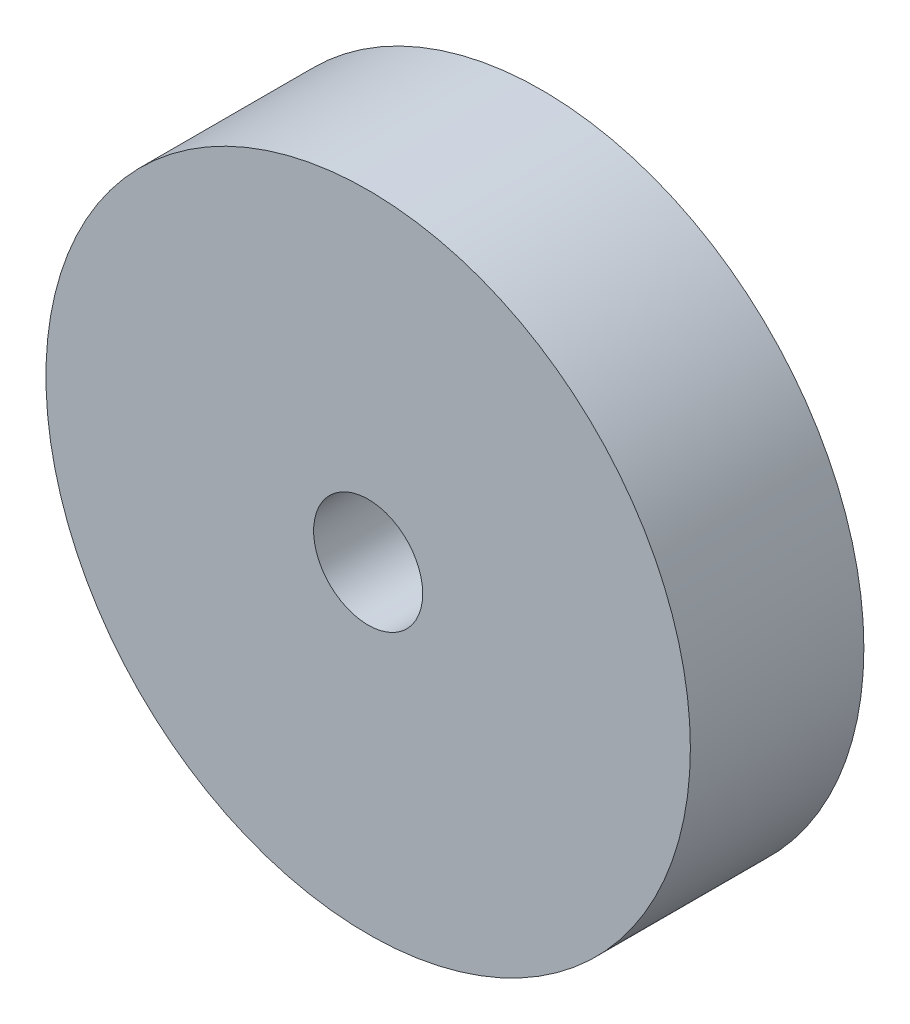
SolidWorks part; units mm, degrees
ref_plane "Front Plane" through (0, 0, 0) normal (0, 0, 1) x (1, 0, 0)
ref_plane "Top Plane" through (0, 0, 0) normal (0, 1, 0) x (1, 0, 0)
ref_plane "Right Plane" through (0, 0, 0) normal (1, 0, 0) x (0, 0, -1)
sketch "Sketch1" plane through (0, 0, 0) normal (0, 0, 1) x (1, 0, 0)
  circle A0 centre (-59.8968, 23.1083) radius 13
  circle A1 centre (-59.8968, 23.1083) radius 1.5
extrude "Boss-Extrude1" add sketch "Sketch1" along normal blind 8
sketch "Sketch2" plane through (0, 0, 8) normal (0, 0, 1) x (1, 0, 0)
  circle A0 centre (-59.8968, 23.1083) radius 2.2
extrude "Cut-Extrude1" cut sketch "Sketch2" against normal blind 10
sketch "Sketch4" plane through (0, 0, 8) normal (0, 0, 1) x (1, 0, 0)
  line L0 (-73.3252, 36.1651) -> (-53.3844, 38.1404)
  line L1 (-53.3844, 38.1404) -> (-46.5179, 36.1651)
  line L2 (-73.3252, 36.1651) -> (-73.3252, 9.7542)
  line L3 (-73.3252, 9.7542) -> (-46.5179, 9.7542)
  line L4 (-46.5179, 36.1651) -> (-46.5179, 9.7542)
extrude "Cut-Extrude2" cut sketch "Sketch4" against normal blind 1
